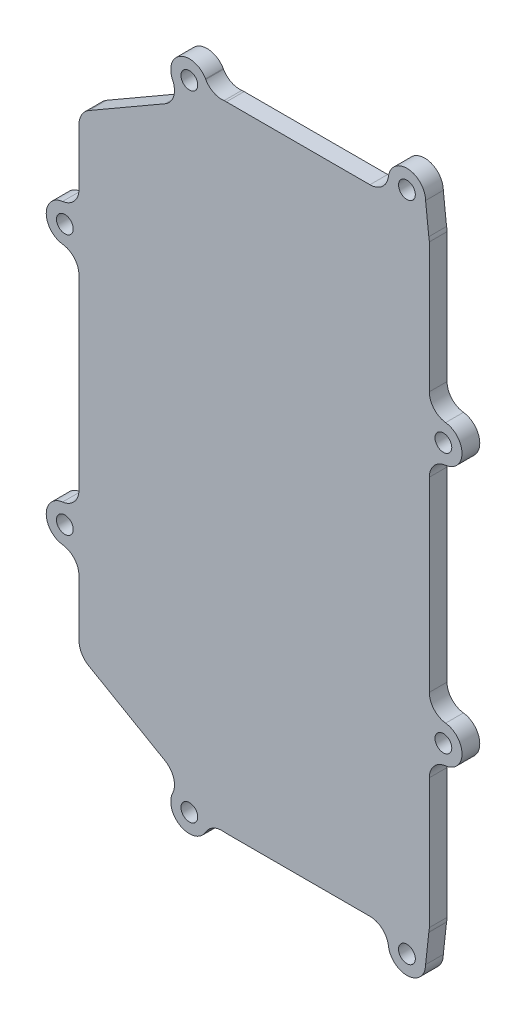
SolidWorks part; units mm, degrees
material "Custom Plastic"
ref_plane "X-Y Datum" through (0, 0, 0) normal (0, 0, 1) x (1, 0, 0)
ref_plane "X-Z Datum" through (0, 0, 0) normal (0, 1, 0) x (1, 0, 0)
ref_plane "Y-Z Datum" through (0, 0, 0) normal (1, 0, 0) x (0, 0, -1)
sketch "Sketch1" plane through (0, 0, 0) normal (0, 0, 1) x (1, 0, 0)
  line L29 (-91.3322, 20.4604) -> (-70.8713, 8.6519)
  line L30 (-94, 40.1546) -> (-94, 25.0802)
  line L37 (-70.8713, 161.3481) -> (-91.3322, 149.5396)
  line L41 (-15.9256, 170) -> (-54.4512, 170)
  line L44 (0, 129.8454) -> (0, 164.666)
  line L49 (-94, 144.9198) -> (-94, 129.8454)
  line L50 (-94, 144.9198) -> (-94, 129.8454)
  line L51 (-59.9785, 172.4312) -> (-60.0427, 172.5424)
  line L52 (-59.9785, 172.4312) -> (-60.0427, 172.5424)
  line L53 (-54.4512, 0) -> (-15.9256, 0)
  line L54 (-0.1268, 165.8222) -> (-1, 173.7827)
  line L55 (-0.1268, 165.8222) -> (-1, 173.7827)
  line L57 (-91.3322, 20.4604) -> (-70.8713, 8.6519)
  line L58 (-94, 40.1546) -> (-94, 25.0802)
  line L65 (-70.8713, 161.3481) -> (-91.3322, 149.5396)
  line L69 (-15.9256, 170) -> (-54.4512, 170)
  line L72 (0, 129.8454) -> (0, 164.666)
  line L81 (-54.4512, 0) -> (-15.9256, 0)
  line L84 (0, 5.334) -> (0, 40.1546)
  line L85 (0, 5.334) -> (0, 40.1546)
  line L86 (-94, 109.9942) -> (-94, 60.0058)
  line L87 (-94, 109.9942) -> (-94, 60.0058)
  line L88 (0, 60.0058) -> (0, 109.9942)
  line L89 (0, 60.0058) -> (0, 109.9942)
  line L90 (-1, -3.7827) -> (-0.1268, 4.1778)
  line L91 (-1, -3.7827) -> (-0.1268, 4.1778)
  line L92 (-60.0427, -2.5424) -> (-59.9785, -2.4312)
  line L93 (-60.0427, -2.5424) -> (-59.9785, -2.4312)
  arc A70 (-94, 25.0802) -> (-91.3322, 20.4604) centre (-88.666, 25.0802) ccw
  arc A71 (-94, 25.0802) -> (-91.3322, 20.4604) centre (-88.666, 25.0802) ccw
  arc A72 (-98.3914, 124.8826) -> (-98.3914, 114.957) centre (-97.7827, 119.9198) ccw
  arc A73 (-98.3914, 124.8826) -> (-98.3914, 114.957) centre (-97.7827, 119.9198) ccw
  arc A74 (-91.3322, 149.5396) -> (-94, 144.9198) centre (-88.666, 144.9198) ccw
  arc A75 (-91.3322, 149.5396) -> (-94, 144.9198) centre (-88.666, 144.9198) ccw
  arc A76 (-60.0427, 172.5424) -> (-68.8719, 167.8609) centre (-64.3732, 170.0431) ccw
  arc A77 (-60.0427, 172.5424) -> (-68.8719, 167.8609) centre (-64.3732, 170.0431) ccw
  arc A79 (-54.4512, 170) -> (-55.069, 169.9641) centre (-54.4512, 164.666) ccw
  arc A81 (-54.4512, 170) -> (-55.069, 169.9641) centre (-54.4512, 164.666) ccw
  arc A83 (-1, 173.7827) -> (-10.9628, 174.3913) centre (-6, 173.7827) ccw
  arc A85 (-1, 173.7827) -> (-10.9628, 174.3913) centre (-6, 173.7827) ccw
  arc A87 (0, 164.666) -> (-0.1268, 165.8222) centre (-5.334, 164.666) ccw
  arc A89 (0, 164.666) -> (-0.1268, 165.8222) centre (-5.334, 164.666) ccw
  arc A91 (4.3913, 114.957) -> (4.3913, 124.8826) centre (3.7827, 119.9198) ccw
  arc A93 (4.3913, 114.957) -> (4.3913, 124.8826) centre (3.7827, 119.9198) ccw
  arc A95 (-0.1268, 4.1778) -> (0, 5.334) centre (-5.334, 5.334) ccw
  arc A97 (-0.1268, 4.1778) -> (0, 5.334) centre (-5.334, 5.334) ccw
  arc A99 (-55.069, 0.0359) -> (-54.4512, 0) centre (-54.4512, 5.334) ccw
  arc A100 (-55.069, 0.0359) -> (-54.4512, 0) centre (-54.4512, 5.334) ccw
  arc A101 (-94, 109.9942) -> (-98.3914, 114.957) centre (-99, 109.9942) ccw
  arc A102 (-94, 109.9942) -> (-98.3914, 114.957) centre (-99, 109.9942) ccw
  arc A103 (-98.3914, 124.8826) -> (-94, 129.8454) centre (-99, 129.8454) ccw
  arc A104 (-98.3914, 124.8826) -> (-94, 129.8454) centre (-99, 129.8454) ccw
  arc A105 (-70.8713, 161.3481) -> (-68.8719, 167.8609) centre (-73.3706, 165.6787) ccw
  arc A106 (-70.8713, 161.3481) -> (-68.8719, 167.8609) centre (-73.3706, 165.6787) ccw
  arc A107 (-59.9785, 172.4312) -> (-55.069, 169.9641) centre (-55.648, 174.9305) ccw
  arc A108 (-59.9785, 172.4312) -> (-55.069, 169.9641) centre (-55.648, 174.9305) ccw
  arc A109 (-15.9256, 170) -> (-10.9628, 174.3913) centre (-15.9256, 175) ccw
  arc A110 (-15.9256, 170) -> (-10.9628, 174.3913) centre (-15.9256, 175) ccw
  arc A111 (0, 129.8454) -> (4.3913, 124.8826) centre (5, 129.8454) ccw
  arc A112 (0, 129.8454) -> (4.3913, 124.8826) centre (5, 129.8454) ccw
  arc A113 (4.3913, 114.957) -> (0, 109.9942) centre (5, 109.9942) ccw
  arc A114 (4.3913, 114.957) -> (0, 109.9942) centre (5, 109.9942) ccw
  arc A115 (-98.3914, 55.043) -> (-98.3914, 45.1174) centre (-97.7827, 50.0802) ccw
  arc A116 (-98.3914, 55.043) -> (-98.3914, 45.1174) centre (-97.7827, 50.0802) ccw
  arc A117 (4.3913, 45.1174) -> (4.3913, 55.043) centre (3.7827, 50.0802) ccw
  arc A118 (4.3913, 45.1174) -> (4.3913, 55.043) centre (3.7827, 50.0802) ccw
  arc A119 (-10.9628, -4.3914) -> (-1, -3.7827) centre (-6, -3.7827) ccw
  arc A120 (-10.9628, -4.3914) -> (-1, -3.7827) centre (-6, -3.7827) ccw
  arc A121 (-68.8719, 2.1391) -> (-60.0427, -2.5424) centre (-64.3732, -0.0431) ccw
  arc A122 (-68.8719, 2.1391) -> (-60.0427, -2.5424) centre (-64.3732, -0.0431) ccw
  arc A123 (-68.8719, 2.1391) -> (-70.8713, 8.6519) centre (-73.3706, 4.3213) ccw
  arc A124 (-68.8719, 2.1391) -> (-70.8713, 8.6519) centre (-73.3706, 4.3213) ccw
  arc A125 (-94, 40.1546) -> (-98.3914, 45.1174) centre (-99, 40.1546) ccw
  arc A126 (-94, 40.1546) -> (-98.3914, 45.1174) centre (-99, 40.1546) ccw
  arc A127 (-98.3914, 55.043) -> (-94, 60.0058) centre (-99, 60.0058) ccw
  arc A128 (-98.3914, 55.043) -> (-94, 60.0058) centre (-99, 60.0058) ccw
  arc A129 (0, 60.0058) -> (4.3913, 55.043) centre (5, 60.0058) ccw
  arc A131 (0, 60.0058) -> (4.3913, 55.043) centre (5, 60.0058) ccw
  arc A133 (4.3913, 45.1174) -> (0, 40.1546) centre (5, 40.1546) ccw
  arc A135 (4.3913, 45.1174) -> (0, 40.1546) centre (5, 40.1546) ccw
  arc A137 (-10.9628, -4.3914) -> (-15.9256, 0) centre (-15.9256, -5) ccw
  arc A138 (-10.9628, -4.3914) -> (-15.9256, 0) centre (-15.9256, -5) ccw
  arc A139 (-55.069, 0.0359) -> (-59.9785, -2.4312) centre (-55.648, -4.9305) ccw
  arc A140 (-55.069, 0.0359) -> (-59.9785, -2.4312) centre (-55.648, -4.9305) ccw
  dimension "D1" = 0
extrude "Boss-Extrude1" add sketch "Sketch1" against normal blind 4.7625
hole_wizard "M4 Clearance Hole1" positions "Sketch2" profile "Sketch3" hole size "M4" standard "ANSI Metric" end condition through all
sketch "Sketch2" plane through (0, 0, -4.7625) normal (0, 0, -1) x (-1, 0, 0)
  point P0 (6, -3.7827)
  point P3 (-3.7827, 50.0802)
  point P6 (-3.7827, 119.9198)
  point P9 (6, 173.7827)
  point P12 (64.3732, 170.0431)
  point P15 (97.7827, 119.9198)
  point P18 (97.7827, 50.0802)
  point P21 (64.3732, -0.0431)
sketch "Sketch3" plane through (-6, -3.7827, -4.7625) normal (1, 0, 0) x (0, 1, 0)
  line L0 (0, 0) -> (0, 4.7625)
  line L1 (0, 4.7625) -> (2.25, 4.7625)
  line L2 (2.25, 4.7625) -> (2.25, 0)
  line L5 (2.25, 0) -> (0, 0)
  line L11 (0, -6.35) -> (0, 107.95) construction
  dimension "Thru Hole Dia." = 4.5
  dimension "Thru Hole Depth" = 4.7625
